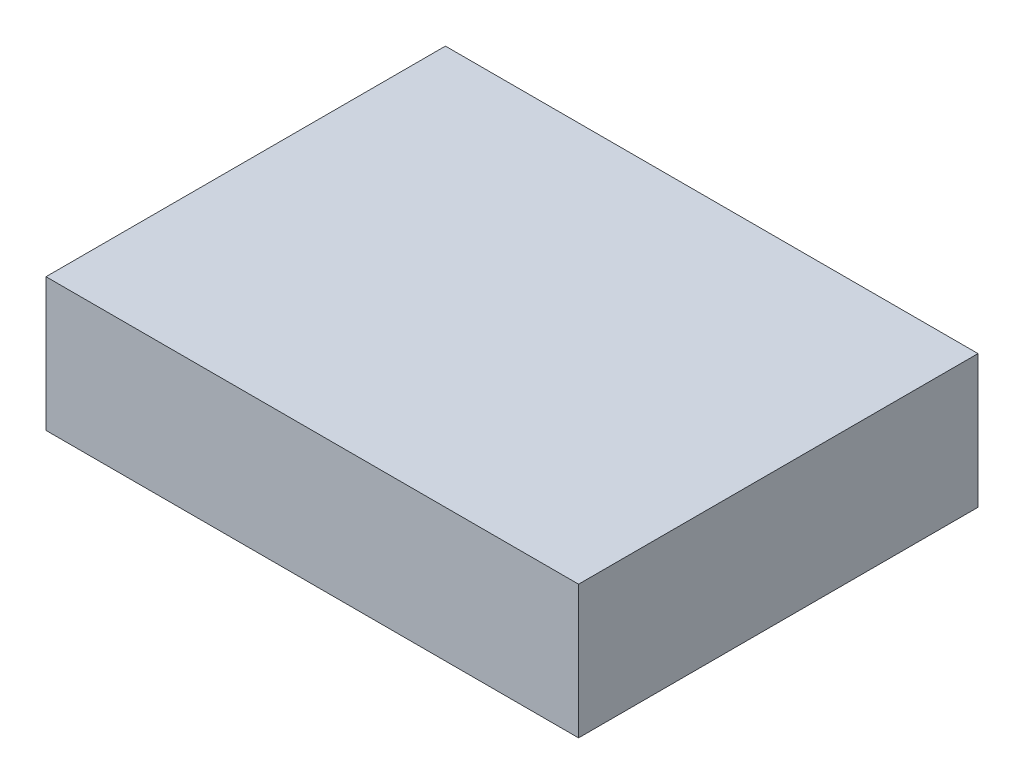
SolidWorks part; units mm, degrees
ref_plane "Front Plane" through (0, 0, 0) normal (0, 0, 1) x (1, 0, 0)
ref_plane "Top Plane" through (0, 0, 0) normal (0, 1, 0) x (1, 0, 0)
ref_plane "Right Plane" through (0, 0, 0) normal (1, 0, 0) x (0, 0, -1)
sketch "Sketch1" plane through (0, 0, 0) normal (0, 1, 0) x (1, 0, 0)
  line L1 (0, 0) -> (50.8, 0)
  line L2 (0, 0) -> (0, 38.1)
  line L3 (0, 38.1) -> (50.8, 38.1)
  line L4 (50.8, 0) -> (50.8, 38.1)
  dimension "D1" = 50.8
  dimension "D2" = 38.1
extrude "Boss-Extrude1" add sketch "Sketch1" along normal blind 12.7
sketch "Sketch2" plane through (0, 12.7, 0) normal (0, 1, 0) x (1, 0, 0)
  text T0 "Sabertooth ESC"
